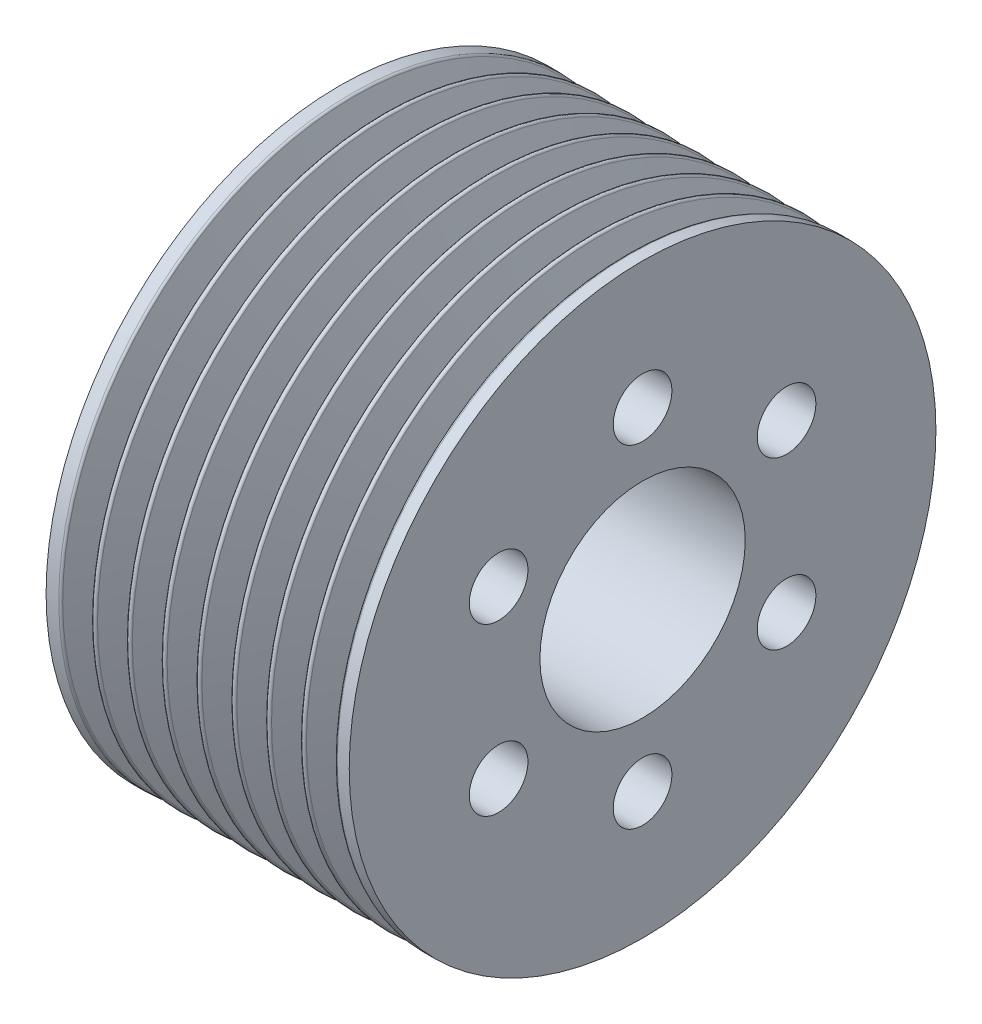
SolidWorks part; units mm, degrees
material "2018 Alloy"
ref_plane "Front Plane" through (0, 0, 0) normal (0, 0, 1) x (1, 0, 0)
ref_plane "Top Plane" through (0, 0, 0) normal (0, 1, 0) x (1, 0, 0)
ref_plane "Right Plane" through (0, 0, 0) normal (1, 0, 0) x (0, 0, -1)
sketch "Sketch1" plane through (0, 0, 0) normal (0, 0, 1) x (1, 0, 0)
  line L0 (49, 10.5) -> (49, 0) construction
  line L1 (49, 10.5) -> (49, 30)
  line L2 (49, 30) -> (18, 30)
  line L3 (18, 30) -> (18, 21.5)
  line L4 (49, 10.5) -> (31.5, 10.5)
  line L5 (0, 0) -> (49, 0) construction
  line L6 (18, 21.5) -> (31.5, 21.5)
  line L8 (0, 8.3175) -> (0, 0) construction
  line L9 (31.5, 10.5) -> (31.5, 21.5)
  dimension "D1" = 31
  dimension "D2" = 60
  dimension "D3" = 31.5
  dimension "D4" = 43
  dimension "D5" = 49
  dimension "D8" = 21
revolve "Revolve1" add sketch "Sketch1" angle 360 about L5
sketch "Sketch2" plane through (0, 0, 0) normal (0, 0, 1) x (1, 0, 0)
  line L0 (47.5451, 29.8355) -> (46.2819, 26.365)
  line L1 (45.7181, 26.365) -> (44.4549, 29.8355)
  line L2 (47.5451, 29.8355) -> (47.6049, 30) construction
  line L3 (49, 30) -> (18, 30) construction
  line L4 (44.4549, 29.8355) -> (44.3951, 30) construction
  line L5 (49, -30) -> (49, 30) construction
  line L6 (47.78, 30) -> (44.22, 30)
  line L7 (0, 0) -> (49, 0) construction
  arc A0 (47.5451, 29.8355) -> (47.78, 30) centre (47.78, 29.75) cw
  arc A1 (44.4549, 29.8355) -> (44.22, 30) centre (44.22, 29.75) ccw
  arc A2 (46.2819, 26.365) -> (45.7181, 26.365) centre (46, 26.4676) cw
  dimension "D2" = 0.25
  dimension "D3" = 0.3
  dimension "D1" = 40
  dimension "D4" = 3.56
  dimension "D5" = 3
revolve "Cut-Revolve1" cut sketch "Sketch2" angle 360 about L7
pattern_linear "LPattern1" count 8 spacing 3.56 along (-1, 0, 0) of "Cut-Revolve1"
sketch "Sketch3" plane through (49, 0, 0) normal (1, 0, 0) x (0, 0, -1)
  circle A0 centre (0, 0) radius 17 construction
  circle A1 centre (0, 17) radius 3
  circle A2 centre (14.7224, 8.5) radius 3
  circle A3 centre (14.7224, -8.5) radius 3
  circle A4 centre (0, -17) radius 3
  circle A5 centre (-14.7224, -8.5) radius 3
  circle A6 centre (-14.7224, 8.5) radius 3
  dimension "D1" = 34
  dimension "D2" = 6
  dimension "D3" = 6
extrude "Cut-Extrude1" cut sketch "Sketch3" against normal up to surface (17.5 mm away) up to face at (31.5, 0, 10.5)
